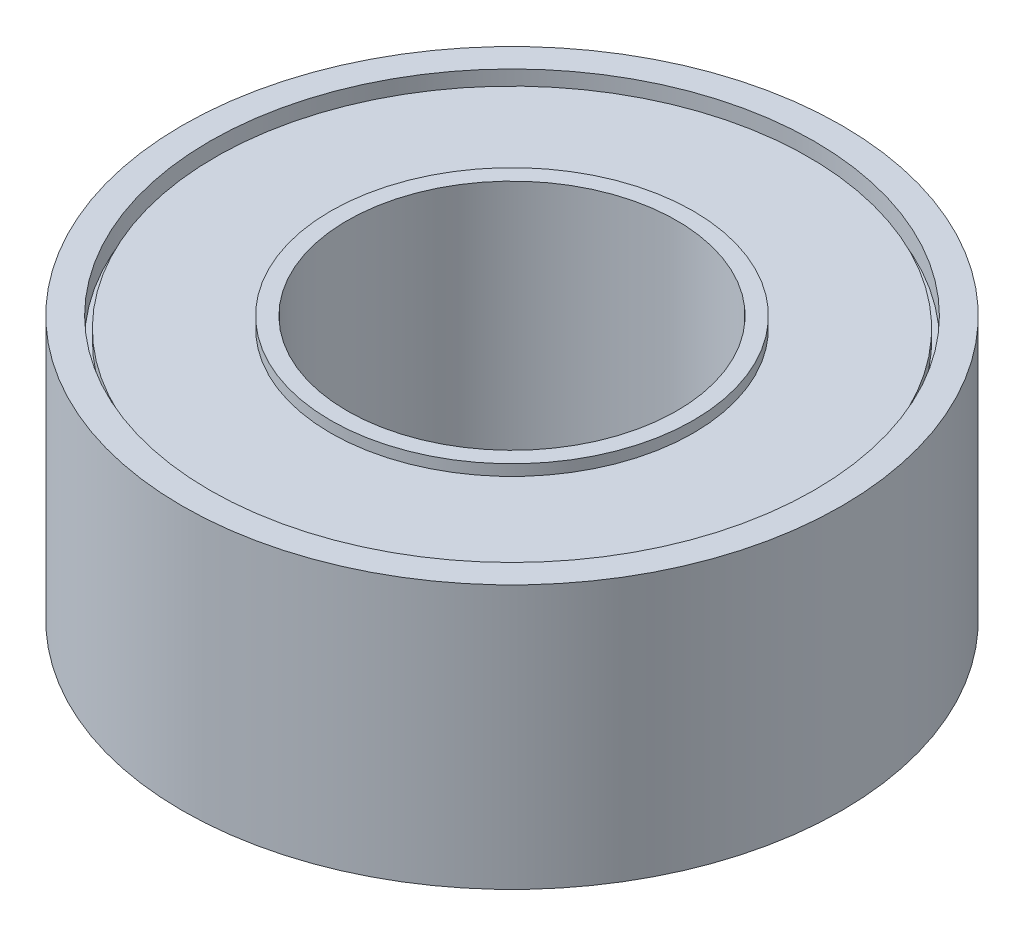
SolidWorks part; units mm, degrees
ref_plane "前视基准面" through (0, 0, 0) normal (0, 0, 1) x (1, 0, 0)
ref_plane "上视基准面" through (0, 0, 0) normal (0, 1, 0) x (1, 0, 0)
ref_plane "右视基准面" through (0, 0, 0) normal (1, 0, 0) x (0, 0, -1)
sketch "草图1" plane through (0, 0, 0) normal (0, 1, 0) x (1, 0, 0)
  circle A0 centre (0, 0) radius 3
  circle A1 centre (0, 0) radius 1.5
extrude "凸台-拉伸1" add sketch "草图1" along normal blind 2.4
sketch "草图2" plane through (0, 2.4, 0) normal (0, 1, 0) x (1, 0, 0)
  circle A0 centre (0, 0) radius 1.65
  circle A1 centre (0, 0) radius 2.75
extrude "切除-拉伸1" cut sketch "草图2" against normal blind 0.1
sketch "草图3" plane through (0, 0, 0) normal (0, -1, 0) x (1, 0, 0)
  circle A0 centre (0, 0) radius 1.65
  circle A1 centre (0, 0) radius 2.75
extrude "切除-拉伸2" cut sketch "草图3" against normal blind 0.1
sketch "草图4" plane through (0, 0.1, 0) normal (0, -1, 0) x (1, 0, 0)
  circle A0 centre (0, 0) radius 2.75
  circle A1 centre (0, 0) radius 2.7
extrude "切除-拉伸3" cut sketch "草图4" against normal blind 0.1
sketch "草图5" plane through (0, 2.3, 0) normal (0, 1, 0) x (1, 0, 0)
  circle A0 centre (0, 0) radius 2.75
  circle A1 centre (0, 0) radius 2.7
extrude "切除-拉伸4" cut sketch "草图5" against normal blind 0.1
